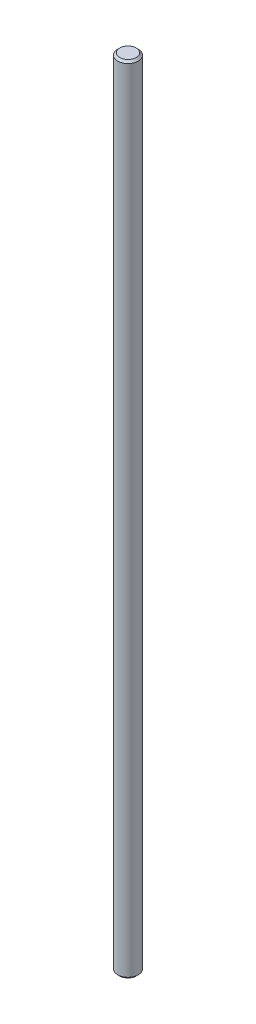
SolidWorks part; units mm, degrees
ref_plane "Front Plane" through (0, 0, 0) normal (0, 0, 1) x (1, 0, 0)
ref_plane "Top Plane" through (0, 0, 0) normal (0, 1, 0) x (1, 0, 0)
ref_plane "Right Plane" through (0, 0, 0) normal (1, 0, 0) x (0, 0, -1)
sketch "Sketch1" plane through (0, 0, 0) normal (0, 1, 0) x (1, 0, 0)
  circle A0 centre (0, 0) radius 5
  dimension "D1" = 10
extrude "Boss-Extrude1" add sketch "Sketch1" along normal mid plane 385
chamfer "Chamfer1" distance 1 angle 45 2 edges at (0, -192.5, 5) (0, 192.5, 5)
